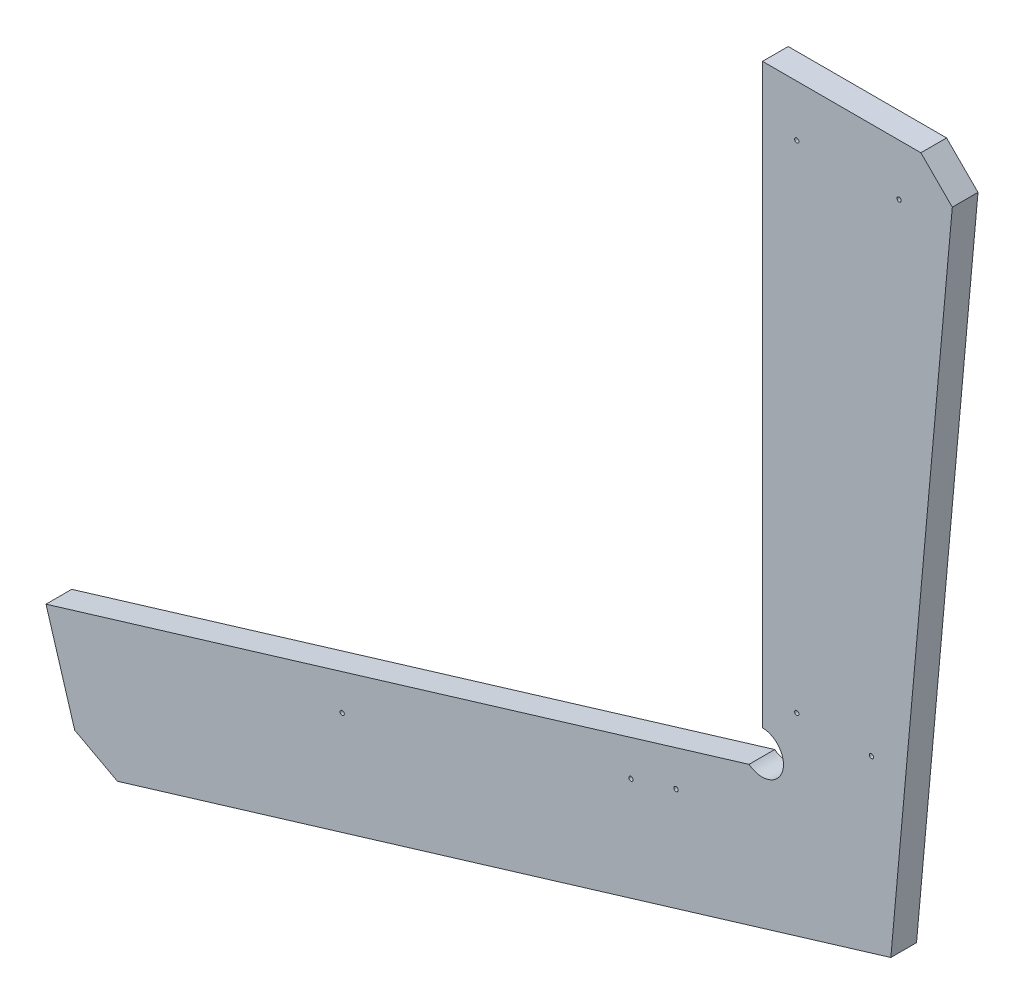
SolidWorks part; units mm, degrees
material "Beech"
ref_plane "Front Plane" through (0, 0, 0) normal (0, 0, 1) x (1, 0, 0)
ref_plane "Top Plane" through (0, 0, 0) normal (0, 1, 0) x (1, 0, 0)
ref_plane "Right Plane" through (0, 0, 0) normal (1, 0, 0) x (0, 0, -1)
sketch "Sketch1" plane through (0, 0, 0) normal (0, 0, 1) x (1, 0, 0)
  line L0 (12.7, 12.7) -> (12.7, -415.1856)
  line L1 (12.7, 12.7) -> (155.4923, 12.7)
  line L2 (155.4923, 12.7) -> (107.8188, -515.0944)
  line L3 (-525.0991, -623.2821) -> (-544.935, -557.7423) construction
  line L6 (2.6872, -443.6415) -> (-518.462, -601.37)
  line L8 (-518.462, -601.37) -> (-489.8291, -695.9756)
  line L9 (-522.1409, -589.2145) -> (-518.462, -601.37) construction
  line L10 (-518.462, -601.37) -> (16.3789, -439.4976) construction
  line L11 (-489.8291, -695.9756) -> (107.8188, -515.0944)
  arc A0 (2.6872, -443.6415) -> (12.7, -415.1856) centre (12.3644, -431.057) ccw
  point P10 (0, 0)
  point P14 (111.5116, -474.2117)
  point P15 (107.8188, -515.0944)
  dimension "D3" = 31.75
  dimension "D1" = 529.9431
  dimension "D4" = 102.6273
  dimension "D5" = 443.757
extrude "Boss-Extrude1" add sketch "Sketch1" against normal blind 19.05
ref_plane "CL" through (0, 0, -9.525) normal (0, 0, 1) x (1, 0, 0)
chamfer "Chamfer1" distance 25.4 angle 45 2 edges at (-489.8291, -695.9756, -9.525) (155.4923, 12.7, -9.525)
hole_wizard "Hole1" [suppressed] positions "Sketch2" profile "Sketch3" legacy
sketch "Sketch2" plane through (0, 10.4243, -184.525) normal (-1, 0, 0) x (0, 0, -1)
  line L8 (155.95, -2.2757) -> (155.95, 437.7664) construction
  line L11 (175, -2.2757) -> (175, 437.7664) construction
  line L15 (155.95, -2.2757) -> (155.95, 107.7348)
  line L16 (155.95, 107.7348) -> (155.95, 217.7454)
  line L17 (155.95, 217.7454) -> (155.95, 327.7559)
  line L18 (155.95, 327.7559) -> (155.95, 437.7664)
  line L20 (175, -2.2757) -> (175, 85.7327)
  line L21 (175, 85.7327) -> (175, 173.7411)
  line L22 (175, 173.7411) -> (175, 261.7496)
  line L23 (175, 261.7496) -> (175, 349.758)
  line L24 (175, 349.758) -> (175, 437.7664)
  line L25 (0, 155.0243) -> (0, 437.7664) construction
  point P36 (155.95, 107.7348)
  point P40 (155.95, 327.7559)
  point P46 (175, 85.7327)
  point P52 (175, 349.758)
  point P77 (-175, 349.758)
  point P80 (-175, 85.7327)
  point P81 (-155.95, 327.7559)
  point P83 (-155.95, 107.7348)
sketch "Sketch3" plane through (0, -97.3105, -28.575) normal (0, 1, 0) x (0, 0, 1)
  line L0 (0, 0) -> (0, 32.7039)
  line L1 (0, 32.7039) -> (1.5875, 31.75)
  line L2 (1.5875, 31.75) -> (1.5875, 4.0177)
  line L3 (1.5875, 4.0177) -> (5.08, 0)
  line L4 (5.08, 0) -> (0, 0)
  line L5 (0, -14.3089) -> (0, 102.4216) construction
  line L6 (0, 32.7039) -> (-1.5875, 31.75) construction
  line L7 (-1.5875, 4.0177) -> (-5.08, 0) construction
  dimension "Diameter" = 3.175
  dimension "Depth" = 31.75
  dimension "C-Sink Diameter" = 10.16
  dimension "C-Sink Angle" = 82
  dimension "Drill Angle" = 118
hole_wizard "Hole2" [suppressed] positions "Sketch4" profile "Sketch5" legacy
sketch "Sketch4" [suppressed] plane through (0, 10.4243, 165.475) normal (-1, 0, 0) x (0, 0, -1)
  line L8 (155.95, -2.2757) -> (155.95, 437.7664) construction
  line L11 (175, -2.2757) -> (175, 437.7664) construction
  line L15 (155.95, -2.2757) -> (155.95, 107.7348)
  line L16 (155.95, 107.7348) -> (155.95, 217.7454)
  line L17 (155.95, 217.7454) -> (155.95, 327.7559)
  line L18 (155.95, 327.7559) -> (155.95, 437.7664)
  line L20 (175, -2.2757) -> (175, 85.7327)
  line L21 (175, 85.7327) -> (175, 173.7411)
  line L22 (175, 173.7411) -> (175, 261.7496)
  line L23 (175, 261.7496) -> (175, 349.758)
  line L24 (175, 349.758) -> (175, 437.7664)
  line L25 (0, 155.0243) -> (0, 437.7664) construction
  point P36 (155.95, 107.7348)
  point P40 (155.95, 327.7559)
  point P46 (175, 85.7327)
  point P52 (175, 349.758)
  point P77 (-175, 349.758)
  point P80 (-175, 85.7327)
  point P81 (-155.95, 327.7559)
  point P83 (-155.95, 107.7348)
sketch "Sketch5" plane through (0, -97.3105, 321.425) normal (0, 1, 0) x (0, 0, 1)
  line L0 (0, 0) -> (0, 32.7039)
  line L1 (0, 32.7039) -> (1.5875, 31.75)
  line L2 (1.5875, 31.75) -> (1.5875, 4.0177)
  line L3 (1.5875, 4.0177) -> (5.08, 0)
  line L4 (5.08, 0) -> (0, 0)
  line L5 (0, -14.3089) -> (0, 102.4216) construction
  line L6 (0, 32.7039) -> (-1.5875, 31.75) construction
  line L7 (-1.5875, 4.0177) -> (-5.08, 0) construction
  dimension "Diameter" = 3.175
  dimension "Depth" = 31.75
  dimension "C-Sink Diameter" = 10.16
  dimension "C-Sink Angle" = 82
  dimension "Drill Angle" = 118
hole_wizard "Hole3" [suppressed] positions "Sketch6" profile "Sketch7" legacy
sketch "Sketch6" plane through (264.6961, -351.0742, -184.525) normal (-0.2897, 0.9571, 0) x (0, 0, -1)
  point P49 (175, 685.961)
  point P51 (175, 549.8373)
  point P53 (175, 413.7135)
  point P67 (81.55, 779.6497)
  point P73 (81.55, 652.3446)
  point P79 (62.5, 662.9534)
  point P83 (62.5, 769.041)
  point P103 (-62.5, 769.041)
  point P105 (-62.5, 662.9534)
  point P106 (-81.55, 652.3446)
  point P109 (-81.55, 779.6497)
  point P110 (-175, 413.7135)
  point P111 (-175, 549.8373)
  point P112 (-175, 685.961)
  point P115 (-82.7375, 600.3846)
  point P117 (0, 600.3846)
  point P119 (82.7375, 600.3846)
  point P129 (0, 376.7378)
  point P131 (-82.7375, 376.7378)
  point P133 (82.7375, 376.7378)
sketch "Sketch7" plane through (-391.8536, -549.7824, -359.525) normal (0, 0, 1) x (-0.9571, -0.2897, 0)
  line L0 (0, 0) -> (0, 32.7039)
  line L1 (0, 32.7039) -> (1.5875, 31.75)
  line L2 (1.5875, 31.75) -> (1.5875, 4.0177)
  line L3 (1.5875, 4.0177) -> (5.08, 0)
  line L4 (5.08, 0) -> (0, 0)
  line L5 (0, -14.3089) -> (0, 102.4216) construction
  line L6 (0, 32.7039) -> (-1.5875, 31.75) construction
  line L7 (-1.5875, 4.0177) -> (-5.08, 0) construction
  dimension "Diameter" = 3.175
  dimension "Depth" = 31.75
  dimension "C-Sink Diameter" = 10.16
  dimension "C-Sink Angle" = 82
  dimension "Drill Angle" = 118
hole_wizard "Hole4" [suppressed] positions "Sketch8" profile "Sketch9" legacy
sketch "Sketch8" [suppressed] plane through (264.6961, -351.0742, 165.475) normal (-0.2897, 0.9571, 0) x (0, 0, -1)
  point P49 (175, 685.961)
  point P51 (175, 549.8373)
  point P53 (175, 413.7135)
  point P67 (81.55, 779.6497)
  point P73 (81.55, 652.3446)
  point P79 (62.5, 662.9534)
  point P83 (62.5, 769.041)
  point P103 (-62.5, 769.041)
  point P105 (-62.5, 662.9534)
  point P106 (-81.55, 652.3446)
  point P109 (-81.55, 779.6497)
  point P110 (-175, 413.7135)
  point P111 (-175, 549.8373)
  point P112 (-175, 685.961)
  point P115 (-82.7375, 600.3846)
  point P117 (0, 600.3846)
  point P119 (82.7375, 600.3846)
  point P129 (0, 376.7378)
  point P131 (-82.7375, 376.7378)
  point P133 (82.7375, 376.7378)
sketch "Sketch9" plane through (-391.8536, -549.7824, -9.525) normal (0, 0, 1) x (-0.9571, -0.2897, 0)
  line L0 (0, 0) -> (0, 32.7039)
  line L1 (0, 32.7039) -> (1.5875, 31.75)
  line L2 (1.5875, 31.75) -> (1.5875, 4.0177)
  line L3 (1.5875, 4.0177) -> (5.08, 0)
  line L4 (5.08, 0) -> (0, 0)
  line L5 (0, -14.3089) -> (0, 102.4216) construction
  line L6 (0, 32.7039) -> (-1.5875, 31.75) construction
  line L7 (-1.5875, 4.0177) -> (-5.08, 0) construction
  dimension "Diameter" = 3.175
  dimension "Depth" = 31.75
  dimension "C-Sink Diameter" = 10.16
  dimension "C-Sink Angle" = 82
  dimension "Drill Angle" = 118
hole_wizard "Hole5" positions "Sketch10" profile "Sketch11" legacy
sketch "Sketch10" plane through (155.2867, 10.4243, -19.05) normal (0, 0, -1) x (-0.09, -0.9959, 0)
  line L0 (48.5061, 138.7859) -> (35.9701, 0) construction
  line L5 (414.5728, 105.7206) -> (405.0235, 0) construction
  line L7 (490.0108, 170.6797) -> (621.0107, 117.7523) construction
  line L12 (503.094, 203.0616) -> (634.0938, 150.1342) construction
  line L16 (586.8736, 410.4234) -> (717.8734, 357.496) construction
  line L19 (597.4602, 127.2674) -> (610.5433, 159.6493) construction
  line L20 (610.5433, 159.6493) -> (694.3229, 367.011) construction
  line L22 (513.5613, 161.1647) -> (526.6445, 193.5466) construction
  line L23 (526.6445, 193.5466) -> (610.424, 400.9084) construction
  point P0 (46.2211, 113.4889)
  point P2 (39.3976, 37.9455)
  point P4 (412.2879, 80.4236)
  point P51 (407.3085, 25.297)
  point P56 (513.5613, 161.1647)
  point P58 (597.4602, 127.2674)
  point P61 (610.5433, 159.6493)
  point P63 (694.3229, 367.011)
  point P66 (526.6445, 193.5466)
  point P68 (610.424, 400.9084)
sketch "Sketch11" plane through (38.1, -25.4, -19.05) normal (1, 0, 0) x (0, 1, 0)
  line L0 (0, 0) -> (0, 39.0539)
  line L1 (0, 39.0539) -> (1.5875, 38.1)
  line L2 (1.5875, 38.1) -> (1.5875, 4.0177)
  line L3 (1.5875, 4.0177) -> (5.08, 0)
  line L4 (5.08, 0) -> (0, 0)
  line L5 (0, -14.3089) -> (0, 102.4216) construction
  line L6 (0, 39.0539) -> (-1.5875, 38.1) construction
  line L7 (-1.5875, 4.0177) -> (-5.08, 0) construction
  dimension "Diameter" = 3.175
  dimension "Depth" = 38.1
  dimension "C-Sink Diameter" = 10.16
  dimension "C-Sink Angle" = 82
  dimension "Drill Angle" = 118
hole_wizard "Hole6" positions "Sketch12" profile "Sketch13" legacy
sketch "Sketch12" plane through (-643.7058, -231.395, 165.475) normal (-0.9571, -0.2897, 0) x (0, 0, -1)
  line L0 (207.775, 377.6924) -> (207.775, 288.0915) construction
  line L4 (108.65, 377.6924) -> (108.65, 288.0915) construction
  line L8 (175, 506.2803) -> (175, 390.3924) construction
  line L12 (94.25, 390.3924) -> (94.25, 377.6924) construction
  line L17 (94.25, 384.0424) -> (217.3, 384.0424) construction
  line L19 (94.25, 384.0424) -> (135.2667, 384.0424)
  line L20 (135.2667, 384.0424) -> (176.2833, 384.0424)
  line L21 (176.2833, 384.0424) -> (217.3, 384.0424)
  line L22 (0, 288.0915) -> (0, 390.3924) construction
  point P39 (108.65, 332.8919)
  point P41 (207.775, 332.8919)
  point P43 (175, 448.3363)
  point P47 (135.2667, 384.0424)
  point P49 (176.2833, 384.0424)
  point P65 (-175, 448.3363)
  point P66 (-135.2667, 384.0424)
  point P67 (-176.2833, 384.0424)
  point P68 (-207.775, 332.8919)
  point P69 (-108.65, 332.8919)
sketch "Sketch13" plane through (-547.2741, -550.0138, 274.125) normal (0, 0, 1) x (0.2897, -0.9571, 0)
  line L0 (0, 0) -> (0, 39.0539)
  line L1 (0, 39.0539) -> (1.5875, 38.1)
  line L2 (1.5875, 38.1) -> (1.5875, 4.0177)
  line L3 (1.5875, 4.0177) -> (5.08, 0)
  line L4 (5.08, 0) -> (0, 0)
  line L5 (0, -14.3089) -> (0, 102.4216) construction
  line L6 (0, 39.0539) -> (-1.5875, 38.1) construction
  line L7 (-1.5875, 4.0177) -> (-5.08, 0) construction
  dimension "Diameter" = 3.175
  dimension "Depth" = 38.1
  dimension "C-Sink Diameter" = 10.16
  dimension "C-Sink Angle" = 82
  dimension "Drill Angle" = 118
